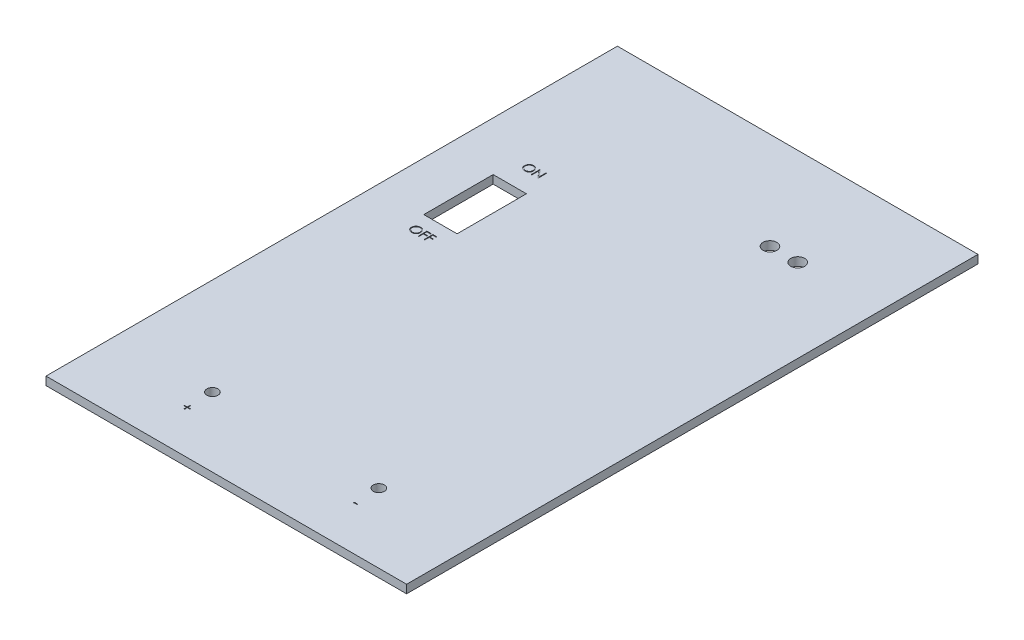
SolidWorks part; units mm, degrees
ref_plane "Front Plane" through (0, 0, 0) normal (0, 0, 1) x (1, 0, 0)
ref_plane "Top Plane" through (0, 0, 0) normal (0, 1, 0) x (1, 0, 0)
ref_plane "Right Plane" through (0, 0, 0) normal (1, 0, 0) x (0, 0, -1)
sketch "Sketch1" plane through (0, 0, 0) normal (0, 1, 0) x (1, 0, 0)
  line L1 (-65, 103) -> (65, 103)
  line L2 (-65, 103) -> (-65, -103)
  line L3 (-65, -103) -> (65, -103)
  line L4 (65, 103) -> (65, -103)
  line L5 (-65, 103) -> (65, -103) construction
  line L6 (-65, -103) -> (65, 103) construction
  point P0 (0, 0)
  dimension "D1" = 206
  dimension "D2" = 130
extrude "Boss-Extrude1" add sketch "Sketch1" along normal blind 3
sketch "Sketch2" plane through (0, 3, 0) normal (0, 1, 0) x (1, 0, 0)
  line L0 (65, -103) -> (65, 103) construction
  line L1 (65, 103) -> (-65, 103) construction
  circle A0 centre (35, 68) radius 2.5
  circle A1 centre (25, 68) radius 2.5
  dimension "D1" = 5
  dimension "D2" = 5
  dimension "D3" = 30
  dimension "D4" = 35
  dimension "D5" = 35
  dimension "D6" = 40
extrude "Cut-Extrude1" cut sketch "Sketch2" against normal blind 10
sketch "Sketch4" plane through (0, 3, 0) normal (0, 1, 0) x (1, 0, 0)
  line L0 (-65, 103) -> (-65, -103) construction
  line L1 (-47.3134, 40.5139) -> (-35.3134, 40.5139)
  line L2 (-47.3134, 40.5139) -> (-47.3134, 15.5139)
  line L3 (-47.3134, 15.5139) -> (-35.3134, 15.5139)
  line L4 (-35.3134, 40.5139) -> (-35.3134, 15.5139)
  line L5 (-47.3134, 40.5139) -> (-35.3134, 15.5139) construction
  line L6 (-47.3134, 15.5139) -> (-35.3134, 40.5139) construction
  line L7 (-65, -103) -> (65, -103) construction
  line L8 (65, -103) -> (65, 103) construction
  circle A0 centre (-30, -78) radius 2
  circle A1 centre (30, -78) radius 2
  point P4 (-41.3134, 28.0139)
  dimension "D1" = 4
  dimension "D2" = 4
  dimension "D3" = 35
  dimension "D4" = 25
  dimension "D5" = 35
  dimension "D6" = 25
  dimension "D7" = 12
  dimension "D8" = 25
extrude "Cut-Extrude2" cut sketch "Sketch4" against normal blind 4
sketch "Sketch6" plane through (0, 3, 0) normal (0, 1, 0) x (1, 0, 0)
  text T0 "OFF"
extrude "Cut-Extrude3" cut sketch "Sketch6" against normal blind 0.2
sketch "Sketch7" plane through (0, 3, 0) normal (0, 1, 0) x (1, 0, 0)
  text T0 "ON"
extrude "Cut-Extrude4" cut sketch "Sketch7" against normal blind 0.2
sketch "Sketch8" plane through (0, 3, 0) normal (0, 1, 0) x (1, 0, 0)
  text T0 "+"
extrude "Cut-Extrude5" cut sketch "Sketch8" against normal blind 0.2
sketch "Sketch9" plane through (0, 3, 0) normal (0, 1, 0) x (1, 0, 0)
  text T0 "-"
extrude "Cut-Extrude6" cut sketch "Sketch9" against normal blind 0.2
equation "\"o.1mm\"=10"
